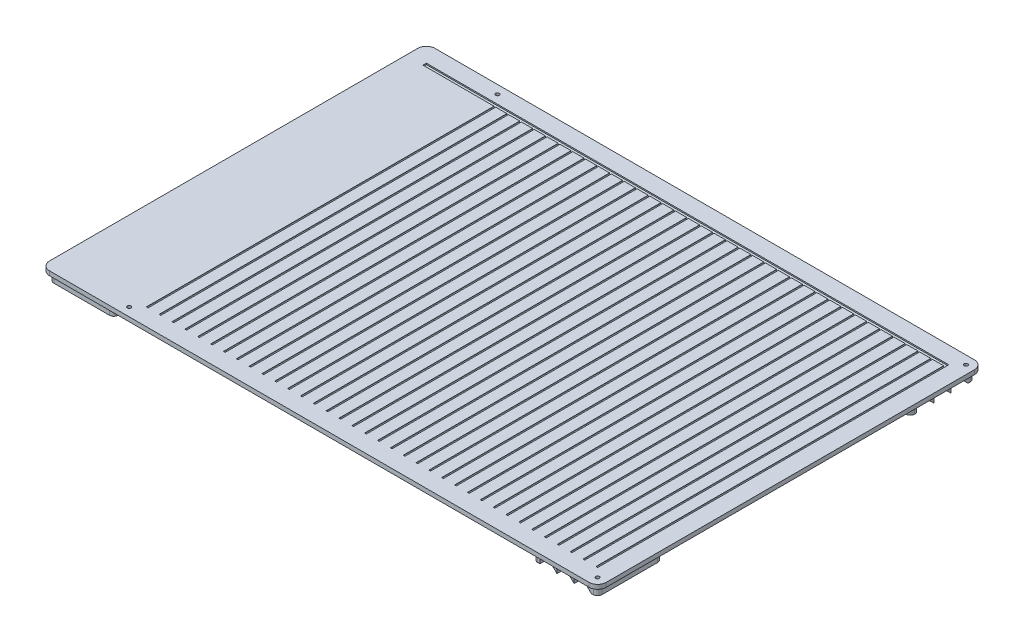
SolidWorks part; units mm, degrees
ref_plane "Front Plane" through (0, 0, 0) normal (0, 0, 1) x (1, 0, 0)
ref_plane "Top Plane" through (0, 0, 0) normal (0, 1, 0) x (1, 0, 0)
ref_plane "Right Plane" through (0, 0, 0) normal (1, 0, 0) x (0, 0, -1)
sketch "Sketch1" plane through (0, 0, 0) normal (0, 1, 0) x (1, 0, 0)
  line L1 (-300, -225) -> (300, -225)
  line L2 (-300, -225) -> (-300, 225) construction
  line L3 (-300, 225) -> (300, 225)
  line L4 (300, -225) -> (300, 225)
  line L5 (-300, -225) -> (300, 225) construction
  line L6 (-300, 225) -> (300, -225) construction
  line L7 (-350, -225) -> (-300, -225)
  line L8 (-350, -225) -> (-350, 225)
  line L9 (-350, 225) -> (-300, 225)
  line L10 (-300, -225) -> (-300, 225) construction
  line L11 (-350, -225) -> (-300, 225) construction
  line L12 (-350, 225) -> (-300, -225) construction
  point P0 (0, 0)
  point P6 (-325, 0)
  dimension "D1" = 450
  dimension "D2" = 600
  dimension "D3" = 50
extrude "Boss-Extrude1" add sketch "Sketch1" along normal blind 5
sketch "Sketch4" plane through (0, 0, 225) normal (0, 0, 1) x (1, 0, 0)
  line L1 (-300, 0) -> (-300, 5) construction
  line L2 (-350, 5) -> (300, 5) construction
  line L4 (280, 5) -> (280, 0) construction
  line L5 (-300, 0) -> (300, 0) construction
  line L6 (300, 5) -> (300, 0) construction
  line L12 (-280, 5) -> (-280, 0) construction
  line L16 (278, 4.5) -> (278, 5)
  line L17 (278, 5) -> (280, 5)
  line L18 (280, 5) -> (280, 4.5)
  line L19 (263, 4.5) -> (263, 5)
  line L20 (263, 5) -> (265, 5)
  line L21 (265, 5) -> (265, 4.5)
  line L22 (278, 4.5) -> (263, 4.5) construction
  line L23 (248, 4.5) -> (248, 5)
  line L24 (248, 5) -> (250, 5)
  line L25 (250, 5) -> (250, 4.5)
  line L26 (233, 4.5) -> (233, 5)
  line L27 (233, 5) -> (235, 5)
  line L28 (235, 5) -> (235, 4.5)
  line L29 (218, 4.5) -> (218, 5)
  line L30 (218, 5) -> (220, 5)
  line L31 (220, 5) -> (220, 4.5)
  line L32 (203, 4.5) -> (203, 5)
  line L33 (203, 5) -> (205, 5)
  line L34 (205, 5) -> (205, 4.5)
  line L35 (188, 4.5) -> (188, 5)
  line L36 (188, 5) -> (190, 5)
  line L37 (190, 5) -> (190, 4.5)
  line L38 (173, 4.5) -> (173, 5)
  line L39 (173, 5) -> (175, 5)
  line L40 (175, 5) -> (175, 4.5)
  line L41 (158, 4.5) -> (158, 5)
  line L42 (158, 5) -> (160, 5)
  line L43 (160, 5) -> (160, 4.5)
  line L44 (143, 4.5) -> (143, 5)
  line L45 (143, 5) -> (145, 5)
  line L46 (145, 5) -> (145, 4.5)
  line L47 (128, 4.5) -> (128, 5)
  line L48 (128, 5) -> (130, 5)
  line L49 (130, 5) -> (130, 4.5)
  line L50 (113, 4.5) -> (113, 5)
  line L51 (113, 5) -> (115, 5)
  line L52 (115, 5) -> (115, 4.5)
  line L53 (98, 4.5) -> (98, 5)
  line L54 (98, 5) -> (100, 5)
  line L55 (100, 5) -> (100, 4.5)
  line L56 (83, 4.5) -> (83, 5)
  line L57 (83, 5) -> (85, 5)
  line L58 (85, 5) -> (85, 4.5)
  line L59 (68, 4.5) -> (68, 5)
  line L60 (68, 5) -> (70, 5)
  line L61 (70, 5) -> (70, 4.5)
  line L62 (53, 4.5) -> (53, 5)
  line L63 (53, 5) -> (55, 5)
  line L64 (55, 5) -> (55, 4.5)
  line L65 (38, 4.5) -> (38, 5)
  line L66 (38, 5) -> (40, 5)
  line L67 (40, 5) -> (40, 4.5)
  line L68 (23, 4.5) -> (23, 5)
  line L69 (23, 5) -> (25, 5)
  line L70 (25, 5) -> (25, 4.5)
  line L71 (8, 4.5) -> (8, 5)
  line L72 (8, 5) -> (10, 5)
  line L73 (10, 5) -> (10, 4.5)
  line L74 (-7, 4.5) -> (-7, 5)
  line L75 (-7, 5) -> (-5, 5)
  line L76 (-5, 5) -> (-5, 4.5)
  line L77 (-22, 4.5) -> (-22, 5)
  line L78 (-22, 5) -> (-20, 5)
  line L79 (-20, 5) -> (-20, 4.5)
  line L80 (-37, 4.5) -> (-37, 5)
  line L81 (-37, 5) -> (-35, 5)
  line L82 (-35, 5) -> (-35, 4.5)
  line L83 (-52, 4.5) -> (-52, 5)
  line L84 (-52, 5) -> (-50, 5)
  line L85 (-50, 5) -> (-50, 4.5)
  line L86 (-67, 4.5) -> (-67, 5)
  line L87 (-67, 5) -> (-65, 5)
  line L88 (-65, 5) -> (-65, 4.5)
  line L89 (-82, 4.5) -> (-82, 5)
  line L90 (-82, 5) -> (-80, 5)
  line L91 (-80, 5) -> (-80, 4.5)
  line L92 (-97, 4.5) -> (-97, 5)
  line L93 (-97, 5) -> (-95, 5)
  line L94 (-95, 5) -> (-95, 4.5)
  line L95 (-112, 4.5) -> (-112, 5)
  line L96 (-112, 5) -> (-110, 5)
  line L97 (-110, 5) -> (-110, 4.5)
  line L98 (-127, 4.5) -> (-127, 5)
  line L99 (-127, 5) -> (-125, 5)
  line L100 (-125, 5) -> (-125, 4.5)
  line L101 (-142, 4.5) -> (-142, 5)
  line L102 (-142, 5) -> (-140, 5)
  line L103 (-140, 5) -> (-140, 4.5)
  line L104 (-157, 4.5) -> (-157, 5)
  line L105 (-157, 5) -> (-155, 5)
  line L106 (-155, 5) -> (-155, 4.5)
  line L107 (-172, 4.5) -> (-172, 5)
  line L108 (-172, 5) -> (-170, 5)
  line L109 (-170, 5) -> (-170, 4.5)
  line L110 (-187, 4.5) -> (-187, 5)
  line L111 (-187, 5) -> (-185, 5)
  line L112 (-185, 5) -> (-185, 4.5)
  line L113 (-202, 4.5) -> (-202, 5)
  line L114 (-202, 5) -> (-200, 5)
  line L115 (-200, 5) -> (-200, 4.5)
  line L116 (-217, 4.5) -> (-217, 5)
  line L117 (-217, 5) -> (-215, 5)
  line L118 (-215, 5) -> (-215, 4.5)
  line L119 (-232, 4.5) -> (-232, 5)
  line L120 (-232, 5) -> (-230, 5)
  line L121 (-230, 5) -> (-230, 4.5)
  line L122 (-247, 4.5) -> (-247, 5)
  line L123 (-247, 5) -> (-245, 5)
  line L124 (-245, 5) -> (-245, 4.5)
  arc A3 (278, 4.5) -> (280, 4.5) centre (279, 4.5) ccw
  arc A4 (263, 4.5) -> (265, 4.5) centre (264, 4.5) ccw
  arc A5 (248, 4.5) -> (250, 4.5) centre (249, 4.5) ccw
  arc A6 (233, 4.5) -> (235, 4.5) centre (234, 4.5) ccw
  arc A7 (218, 4.5) -> (220, 4.5) centre (219, 4.5) ccw
  arc A8 (203, 4.5) -> (205, 4.5) centre (204, 4.5) ccw
  arc A9 (188, 4.5) -> (190, 4.5) centre (189, 4.5) ccw
  arc A10 (173, 4.5) -> (175, 4.5) centre (174, 4.5) ccw
  arc A11 (158, 4.5) -> (160, 4.5) centre (159, 4.5) ccw
  arc A12 (143, 4.5) -> (145, 4.5) centre (144, 4.5) ccw
  arc A13 (128, 4.5) -> (130, 4.5) centre (129, 4.5) ccw
  arc A14 (113, 4.5) -> (115, 4.5) centre (114, 4.5) ccw
  arc A15 (98, 4.5) -> (100, 4.5) centre (99, 4.5) ccw
  arc A16 (83, 4.5) -> (85, 4.5) centre (84, 4.5) ccw
  arc A17 (68, 4.5) -> (70, 4.5) centre (69, 4.5) ccw
  arc A18 (53, 4.5) -> (55, 4.5) centre (54, 4.5) ccw
  arc A19 (38, 4.5) -> (40, 4.5) centre (39, 4.5) ccw
  arc A20 (23, 4.5) -> (25, 4.5) centre (24, 4.5) ccw
  arc A21 (8, 4.5) -> (10, 4.5) centre (9, 4.5) ccw
  arc A22 (-7, 4.5) -> (-5, 4.5) centre (-6, 4.5) ccw
  arc A23 (-22, 4.5) -> (-20, 4.5) centre (-21, 4.5) ccw
  arc A24 (-37, 4.5) -> (-35, 4.5) centre (-36, 4.5) ccw
  arc A25 (-52, 4.5) -> (-50, 4.5) centre (-51, 4.5) ccw
  arc A26 (-67, 4.5) -> (-65, 4.5) centre (-66, 4.5) ccw
  arc A27 (-82, 4.5) -> (-80, 4.5) centre (-81, 4.5) ccw
  arc A28 (-97, 4.5) -> (-95, 4.5) centre (-96, 4.5) ccw
  arc A29 (-112, 4.5) -> (-110, 4.5) centre (-111, 4.5) ccw
  arc A30 (-127, 4.5) -> (-125, 4.5) centre (-126, 4.5) ccw
  arc A31 (-142, 4.5) -> (-140, 4.5) centre (-141, 4.5) ccw
  arc A32 (-157, 4.5) -> (-155, 4.5) centre (-156, 4.5) ccw
  arc A33 (-172, 4.5) -> (-170, 4.5) centre (-171, 4.5) ccw
  arc A34 (-187, 4.5) -> (-185, 4.5) centre (-186, 4.5) ccw
  arc A35 (-202, 4.5) -> (-200, 4.5) centre (-201, 4.5) ccw
  arc A36 (-217, 4.5) -> (-215, 4.5) centre (-216, 4.5) ccw
  arc A37 (-232, 4.5) -> (-230, 4.5) centre (-231, 4.5) ccw
  arc A38 (-247, 4.5) -> (-245, 4.5) centre (-246, 4.5) ccw
  point P0 (-300, 0)
  dimension "D4" = 1
  dimension "D2" = 20
  dimension "D1" = 20
  dimension "D3" = 0.5
  dimension "D6" = 15
  dimension "D5" = 36
extrude "Cut-Extrude2" cut sketch "Sketch4" against normal offset from surface (410 mm away) 20 from offset 20 up to face at (-25, 2.5, -225) offset against normal yes
sketch "Sketch6" plane through (280, 0, 0) normal (-1, 0, 0) x (0, 0, 1)
  line L0 (-205, 5) -> (-201, 5)
  line L1 (-205, 5) -> (205, 5) construction
  line L2 (-201, 5) -> (-201, 3.5)
  line L4 (-205, 5) -> (-205, 3.5)
  line L6 (-201, 3.5) -> (-205, 3.5)
  line L7 (-205, 3.5) -> (-205, 4.5) construction
  line L8 (-205, 3.5) -> (-205, 4.5)
  point P8 (0, 0)
  line M4 (-205, 5) -> (-205, 4.5)
  line M5 (-205, 4.5) -> (205, 4.5)
  line M7 (205, 5) -> (-205, 5)
  dimension "D1" = 4
extrude "Cut-Extrude3" cut sketch "Sketch6" along normal offset from surface (610 mm away) 20 contours L6 L2 L4 M5 | L2 M7 M4 M5 up to face at (-350, 2.5, 0)
sketch "Sketch9" plane through (0, 5, 0) normal (0, 1, 0) x (1, 0, 0)
  line L0 (280, 205) -> (300, 225) construction
  line L1 (-247, 205) -> (-267, 225) construction
  line L2 (-330, 205) -> (280, 205) construction
  line L3 (300, 225) -> (-350, 225) construction
  line L4 (-247, 201) -> (-247, -205) construction
  line L5 (-247, -205) -> (-267, -225) construction
  line L6 (-350, -225) -> (300, -225) construction
  line L7 (280, -205) -> (300, -225) construction
  point P4 (290, 215)
  point P12 (-257, 215)
  point P18 (-257, -215)
  point P21 (290, -215)
  dimension "D1" = 45
  dimension "D2" = 45
fillet "Fillet3" radius 10 4 edges at (300, 2.5, -225) (300, 2.5, 225) (-350, 2.5, -225) (-350, 2.5, 225)
sketch "Sketch16" plane through (0, 0, 0) normal (0, -1, 0) x (1, 0, 0)
  line L0 (-340, -220) -> (290, -220) construction
  line L1 (295, -215) -> (295, 215) construction
  line L2 (290, 220) -> (-340, 220) construction
  line L3 (-345, 215) -> (-345, -215) construction
  line L4 (-340, -225) -> (290, -225)
  line L5 (300, -215) -> (300, 215)
  line L6 (290, 225) -> (-340, 225)
  line L7 (-350, 215) -> (-350, -215)
  line L8 (-340, -225) -> (290, -225) construction
  line L9 (300, -215) -> (300, 215) construction
  line L10 (290, 225) -> (-340, 225) construction
  line L11 (-350, 215) -> (-350, -215) construction
  line L12 (-345, 215) -> (-345, 150)
  line L13 (-340, 220) -> (-275, 220)
  line L14 (-345, 0) -> (49655, 0) construction
  line L15 (-25, -220) -> (-25, 49780) construction
  line L16 (-307.5, 220) -> (-307.5, -49780) construction
  line L17 (-345, 182.5) -> (49655, 182.5) construction
  line L18 (-340, 145) -> (-275, 145)
  line L19 (-270, 215) -> (-270, 150)
  line L20 (-345, -215) -> (-345, -150)
  line L21 (-345, -182.5) -> (49655, -182.5) construction
  line L22 (-270, -215) -> (-270, -150)
  line L23 (-340, -145) -> (-275, -145)
  line L24 (-340, -220) -> (-275, -220)
  line L25 (290, 220) -> (225, 220)
  line L26 (257.5, 220) -> (257.5, -49780) construction
  line L27 (290, 145) -> (225, 145)
  line L28 (295, 215) -> (295, 150)
  line L29 (220, 150) -> (220, 215)
  line L30 (290, -220) -> (225, -220)
  line L31 (295, -215) -> (295, -150)
  line L32 (290, -145) -> (225, -145)
  line L33 (220, -215) -> (220, -150)
  arc A0 (290, -220) -> (295, -215) centre (290, -215) ccw construction
  arc A1 (295, 215) -> (290, 220) centre (290, 215) ccw construction
  arc A2 (-340, 220) -> (-345, 215) centre (-340, 215) ccw construction
  arc A3 (-345, -215) -> (-340, -220) centre (-340, -215) ccw construction
  arc A4 (290, -225) -> (300, -215) centre (290, -215) ccw
  arc A5 (300, 215) -> (290, 225) centre (290, 215) ccw
  arc A6 (-340, 225) -> (-350, 215) centre (-340, 215) ccw
  arc A7 (-350, -215) -> (-340, -225) centre (-340, -215) ccw
  arc A8 (290, -225) -> (300, -215) centre (290, -215) ccw construction
  arc A9 (300, 215) -> (290, 225) centre (290, 215) ccw construction
  arc A10 (-340, 225) -> (-350, 215) centre (-340, 215) ccw construction
  arc A11 (-350, -215) -> (-340, -225) centre (-340, -215) ccw construction
  arc A12 (-340, 220) -> (-345, 215) centre (-340, 215) ccw
  arc A13 (-275, 220) -> (-270, 215) centre (-275, 215) cw
  arc A14 (-275, 145) -> (-270, 150) centre (-275, 150) ccw
  arc A15 (-340, 145) -> (-345, 150) centre (-340, 150) cw
  arc A16 (-345, -215) -> (-340, -220) centre (-340, -215) ccw
  arc A17 (-345, -150) -> (-340, -145) centre (-340, -150) cw
  arc A18 (-270, -215) -> (-275, -220) centre (-275, -215) cw
  arc A19 (-270, -150) -> (-275, -145) centre (-275, -150) ccw
  arc A20 (290, 220) -> (295, 215) centre (290, 215) cw
  arc A21 (290, 145) -> (295, 150) centre (290, 150) ccw
  arc A22 (225, 220) -> (220, 215) centre (225, 215) ccw
  arc A23 (225, 145) -> (220, 150) centre (225, 150) cw
  arc A24 (295, -215) -> (290, -220) centre (290, -215) cw
  arc A25 (225, -220) -> (220, -215) centre (225, -215) cw
  arc A26 (295, -150) -> (290, -145) centre (290, -150) ccw
  arc A27 (225, -145) -> (220, -150) centre (225, -150) ccw
  point P30 (-25, -220)
  point P34 (-345, 0)
  point P36 (-307.5, 220)
  point P39 (-345, 182.5)
  point P49 (-345, -182.5)
  point P62 (257.5, 220)
  point P79 (286.7019, -141.702)
  point P82 (0, 0)
  point P83 (0, 0)
  point P84 (0, 0)
  dimension "D3" = 75
  dimension "D2" = 5
extrude "Boss-Extrude2" add sketch "Sketch16" along normal blind 10 contours L22 A19 L23 A17 L20 A16 L24 A18 | A15 L18 A14 L19 A13 L13 A12 L12 | A23 L27 A21 L28 A20 L25 A22 L29 | L32 A27 L33 A25 L30 A24 L31 A26
sketch "Sketch17" plane through (0, 0, -220) normal (0, 0, -1) x (-1, 0, 0)
  line L2 (337.5, -10) -> (327.5, 0)
  line L5 (327.5, 0) -> (317.5, 0)
  line L6 (317.5, 0) -> (317.5, -10)
  line L9 (317.5, -10) -> (307.5, 0)
  line L10 (340, -10) -> (275, -10) construction
  line L11 (-290, 0) -> (340, 0) construction
  line L13 (317.5, -10) -> (337.5, -10)
  line L14 (340, -10) -> (340, 0) construction
  line L15 (297.5, -10) -> (317.5, -10)
  line L16 (297.5, 0) -> (297.5, -10)
  line L17 (307.5, 0) -> (297.5, 0)
  line L18 (297.5, -10) -> (287.5, 0)
  line L19 (277.5, -10) -> (297.5, -10)
  line L20 (277.5, 0) -> (277.5, -10)
  line L21 (287.5, 0) -> (277.5, 0)
  line L22 (337.5, -10) -> (317.5, -10) construction
  point P6 (336.7005, -10)
  dimension "D1" = 2.5
  dimension "D2" = 45
  dimension "D4" = 3
  dimension "D3" = 10
  dimension "D5" = 20
extrude "Cut-Extrude4" cut sketch "Sketch17" against normal up to surface (75 mm away) contours L6 L13 L2 L5 | L9 L17 L16 L15 | L18 L21 L20 L19 up to face at (-307.5, -5, -145)
sketch "Sketch18" plane through (-345, 0, 0) normal (-1, 0, 0) x (0, 0, 1)
  line L0 (212.5, -10) -> (202.5, 0)
  line L1 (215, -10) -> (150, -10) construction
  line L2 (215, 0) -> (150, 0) construction
  line L3 (202.5, 0) -> (192.5, 0)
  line L4 (192.5, 0) -> (192.5, -10)
  line L5 (192.5, -10) -> (212.5, -10)
  line L6 (215, -10) -> (215, 0) construction
  line L7 (192.5, -10) -> (182.5, 0)
  line L8 (172.5, -10) -> (192.5, -10)
  line L9 (182.5, 0) -> (172.5, 0)
  line L10 (172.5, 0) -> (172.5, -10)
  line L11 (172.5, -10) -> (162.5, 0)
  line L12 (152.5, -10) -> (172.5, -10)
  line L13 (162.5, 0) -> (152.5, 0)
  line L14 (152.5, 0) -> (152.5, -10)
  line L15 (212.5, -10) -> (192.5, -10) construction
  line M5 (215, 0) -> (150, 0)
  line M7 (150, -10) -> (215, -10)
  dimension "D1" = 45
  dimension "D2" = 2.5
  dimension "D3" = 10
  dimension "D5" = 20
  dimension "D4" = 3
extrude "Cut-Extrude5" cut sketch "Sketch18" against normal up to surface (75 mm away) contours L4 L0 M5 M7 | L10 L7 M5 M7 | L14 L11 M5 M7 up to face at (-270, -5, 182.5)
sketch "Sketch19" plane through (0, 0, 220) normal (0, 0, 1) x (1, 0, 0)
  line L0 (287.5, -10) -> (277.5, 0)
  line L1 (290, -10) -> (225, -10) construction
  line L2 (290, 0) -> (225, 0) construction
  line L3 (277.5, 0) -> (267.5, 0)
  line L4 (267.5, 0) -> (267.5, -10)
  line L5 (267.5, -10) -> (287.5, -10)
  line L6 (290, -10) -> (290, 0) construction
  line L7 (267.5, -10) -> (257.5, 0)
  line L8 (247.5, -10) -> (267.5, -10)
  line L9 (247.5, 0) -> (247.5, -10)
  line L10 (257.5, 0) -> (247.5, 0)
  line L11 (247.5, -10) -> (237.5, 0)
  line L12 (227.5, -10) -> (247.5, -10)
  line L13 (227.5, 0) -> (227.5, -10)
  line L14 (237.5, 0) -> (227.5, 0)
  line L15 (287.5, -10) -> (267.5, -10) construction
  line M5 (290, 0) -> (225, 0)
  line M7 (225, -10) -> (290, -10)
  dimension "D1" = 45
  dimension "D2" = 2.5
  dimension "D3" = 10
  dimension "D5" = 20
  dimension "D4" = 3
extrude "Cut-Extrude6" cut sketch "Sketch19" against normal up to surface (75 mm away) contours L4 L0 M5 M7 | L9 L7 M5 M7 | L13 L11 M5 M7 up to face at (257.5, -5, 145)
sketch "Sketch20" plane through (295, 0, 0) normal (1, 0, 0) x (0, 0, -1)
  line L0 (212.5, -10) -> (202.5, 0)
  line L1 (215, -10) -> (150, -10) construction
  line L2 (215, 0) -> (150, 0) construction
  line L3 (202.5, 0) -> (192.5, 0)
  line L4 (192.5, 0) -> (192.5, -10)
  line L5 (192.5, -10) -> (212.5, -10)
  line L6 (215, -10) -> (215, 0) construction
  line L7 (192.5, -10) -> (182.5, 0)
  line L8 (172.5, -10) -> (192.5, -10)
  line L9 (172.5, 0) -> (172.5, -10)
  line L10 (182.5, 0) -> (172.5, 0)
  line L11 (172.5, -10) -> (162.5, 0)
  line L12 (152.5, -10) -> (172.5, -10)
  line L13 (152.5, 0) -> (152.5, -10)
  line L14 (162.5, 0) -> (152.5, 0)
  line L15 (212.5, -10) -> (192.5, -10) construction
  line M5 (215, 0) -> (150, 0)
  line M7 (150, -10) -> (215, -10)
  dimension "D1" = 45
  dimension "D2" = 10
  dimension "D3" = 2.5
  dimension "D5" = 20
  dimension "D4" = 3
extrude "Cut-Extrude7" cut sketch "Sketch20" against normal up to surface (75 mm away) contours L4 L0 M5 M7 | L9 L7 M5 M7 | L13 L11 M5 M7 up to face at (220, -5, -182.5)
hole_wizard "Tap Drill for M5x0.8 Tap3" positions "3DSketch5" profile "Sketch21" hole size "M5x0.8" standard "ANSI Metric" end condition through all
sketch3d "3DSketch5"
  point P0 (-257, 5, 215)
  point P3 (-257, 5, -215)
  point P6 (290, 5, -215)
  point P9 (290, 5, 215)
sketch "Sketch21" plane through (-257, 5, 215) normal (1, 0, 0) x (0, 0, 1)
  line L0 (0, 0) -> (0, 15)
  line L1 (0, 15) -> (2.1, 15)
  line L2 (2.1, 15) -> (2.1, 0)
  line L5 (2.1, 0) -> (0, 0)
  line L11 (0, -6.35) -> (0, 107.95) construction
  dimension "Thru Hole Dia." = 4.2
  dimension "Thru Hole Depth" = 15
equation "\"half_plate_thickness\"= 0.5cm'Total plate thickness = 1 cm"
equation "\"plate_length\"= 60cm'Parallel to x-axis"
equation "\"plate_width\"= 45cm'Parallel to z-axis"
equation "\"D1@Sketch1\"=\"plate_width\""
equation "\"D2@Sketch1\"=\"plate_length\""
equation "\"D1@Boss-Extrude1\"=\"half_plate_thickness\""
equation "\"electronics_box_length\"= 5cm'Parallel to x-axis"
equation "\"D3@Sketch1\"=\"electronics_box_length\""
equation "\"wall_width\"= 2cm'Same value for wall_length"
equation "\"eds_radius\"= 1mm"
equation "\"D2@Sketch4\"=\"wall_width\""
equation "\"eds_spacing\"= 15mm"
equation "\"general_tolerance\"= 0.5mm"
equation "\"D1@Sketch4\"=\"wall_width\""
equation "\"D3@Sketch4\"=\"general_tolerance\""
equation "\"D4@Sketch4\"=\"eds_radius\""
equation "\"D6@Sketch4\"=\"eds_spacing\""
equation "\"eds_count\" = 36"
equation "\"D5@Sketch4\"=\"eds_count\""
equation "\"D19@Cut-Extrude2\"=\"wall_width\""
equation "\"D1@Cut-Extrude2\"=\"wall_width\""
equation "\"D1@Sketch6\"=\"eds_radius\"*4"
equation "\"D1@Cut-Extrude3\"=\"wall_width\""
equation "\"plate_fillet_radius\"= 10mm"
equation "\"tooth_height\"= 1cm"
equation "\"D1@Fillet3\"=\"plate_fillet_radius\""
equation "\"tooth_offset\"= 0.5cm"
equation "\"D2@Sketch16\"=\"tooth_offset\""
equation "\"tooth_patch_width\"= 7.5cm"
equation "\"D3@Sketch16\"=\"tooth_patch_width\""
equation "\"D1@Boss-Extrude2\"=\"tooth_height\""
